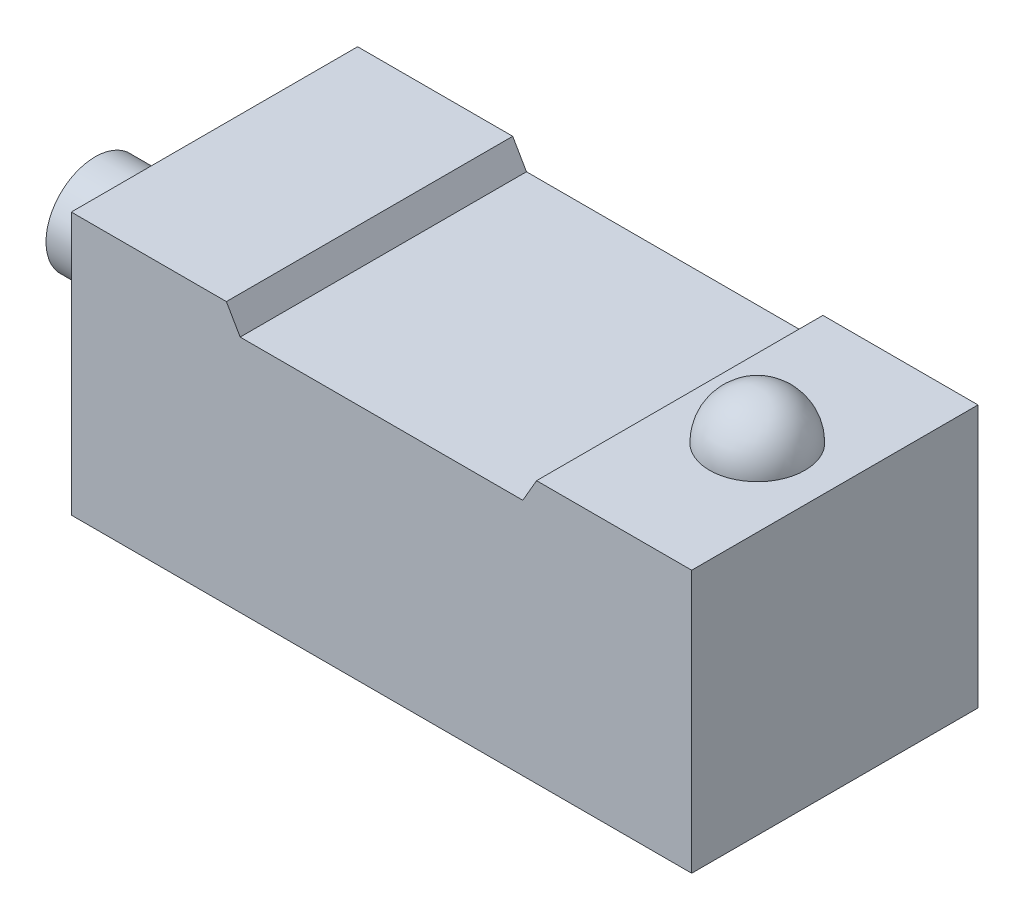
SolidWorks part; units mm, degrees
ref_plane "前视基准面" through (0, 0, 0) normal (0, 0, 1) x (1, 0, 0)
ref_plane "上视基准面" through (0, 0, 0) normal (0, 1, 0) x (1, 0, 0)
ref_plane "右视基准面" through (0, 0, 0) normal (1, 0, 0) x (0, 0, -1)
sketch "草图1" plane through (0, 0, 0) normal (0, 1, 0) x (1, 0, 0)
  line L1 (-13, -6) -> (13, -6)
  line L2 (-13, -6) -> (-13, 6)
  line L3 (-13, 6) -> (13, 6)
  line L4 (13, -6) -> (13, 6)
  line L5 (-13, -6) -> (13, 6) construction
  line L6 (-13, 6) -> (13, -6) construction
  point P0 (0, 0)
  dimension "D1" = 26
  dimension "D2" = 12
extrude "拉伸1" add sketch "草图1" along normal blind 11
sketch "草图2" plane through (0, 11, 0) normal (0, 1, 0) x (1, 0, 0)
  line L1 (-6.5, -7.5) -> (6.5, -7.5)
  line L2 (-6.5, -7.5) -> (-6.5, 7.5)
  line L3 (-6.5, 7.5) -> (6.5, 7.5)
  line L4 (6.5, -7.5) -> (6.5, 7.5)
  line L5 (-6.5, -7.5) -> (6.5, 7.5) construction
  line L6 (-6.5, 7.5) -> (6.5, -7.5) construction
  point P0 (0, 0)
  dimension "D1" = 13
  dimension "D2" = 15
extrude "拉伸2" cut sketch "草图2" against normal blind 1 draft 30
sketch "草图3" plane through (0, 0, 0) normal (0, 0, 1) x (1, 0, 0)
  line L0 (9.75, 13) -> (9.75, 9)
  line L1 (6.5, 11) -> (13, 11) construction
  line L2 (9.75, 11) -> (9.75, 13) construction
  line L3 (9.75, 11) -> (9.75, 8.5787) construction
  arc A0 (9.75, 9) -> (9.75, 13) centre (9.75, 11) ccw
  dimension "D1" = 4
revolve "旋转1" add sketch "草图3" angle 360 about L0
sketch "草图4" plane through (-13, 0, 0) normal (-1, 0, 0) x (0, 0, 1)
  circle A0 centre (0, 5.4455) radius 2.0601
extrude "拉伸3" add sketch "草图4" along normal blind 5
